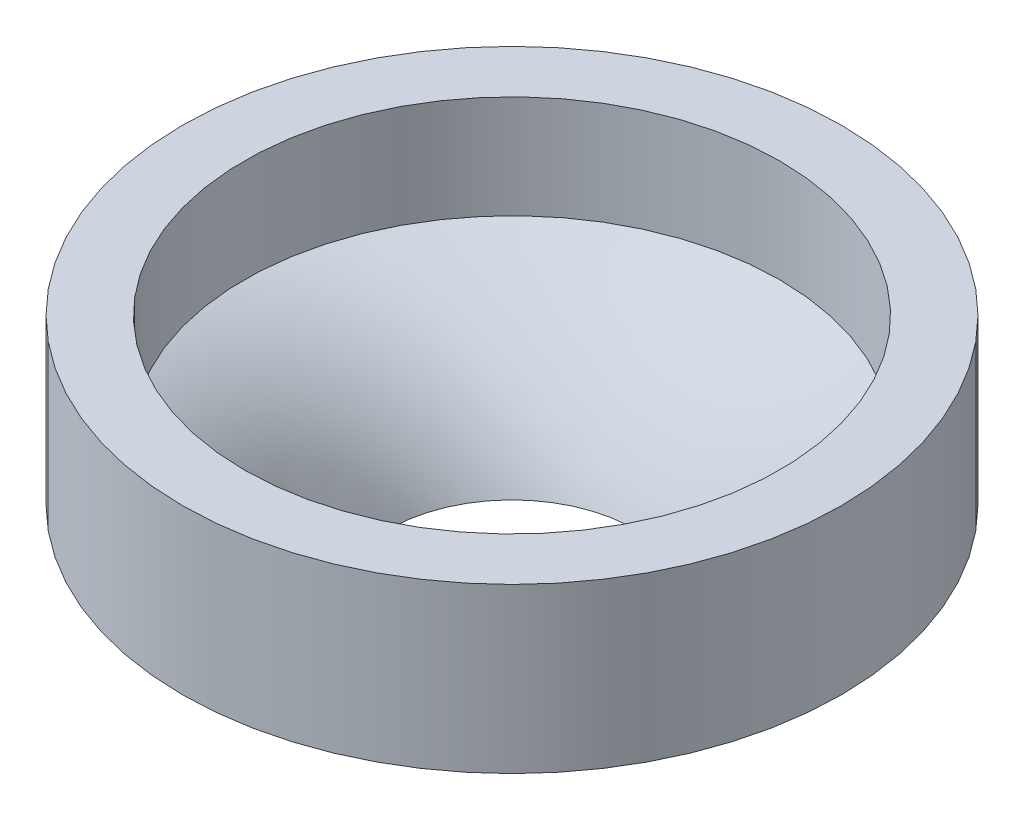
SolidWorks part; units mm, degrees
ref_plane "Front Plane" through (0, 0, 0) normal (0, 0, 1) x (1, 0, 0)
ref_plane "Top Plane" through (0, 0, 0) normal (0, 1, 0) x (1, 0, 0)
ref_plane "Right Plane" through (0, 0, 0) normal (1, 0, 0) x (0, 0, -1)
sketch "Sketch2" plane through (0, 0, 0) normal (1, 0, 0) x (0, 0, -1)
  line L0 (0, 40.9053) -> (0, -41.6717) construction
  line L1 (-79.0564, -40.2605) -> (-79.0564, -32.3059)
  line L2 (-76.0564, -37.3059) -> (-76.0564, -44.3059) construction
  line L3 (-69.0564, -44.3059) -> (-76.0564, -44.3059) construction
  line L4 (-76.0564, -37.3059) -> (-76.0564, -32.3059)
  line L5 (-79.0564, -32.3059) -> (-76.0564, -32.3059)
  line L6 (-69.0564, -44.3059) -> (-72.1486, -44.3059)
  line L7 (-63.0564, -32.3059) -> (-63.0564, -42.3059) construction
  arc A1 (-79.0564, -40.2605) -> (-72.1486, -44.3059) centre (-77.8197, -46.0692) cw
  arc A2 (-79.0564, -40.2605) -> (-71.9975, -44.8977) centre (-77.8197, -46.0692) cw construction
  arc A3 (-76.0564, -37.3059) -> (-69.0564, -44.3059) centre (-77.8197, -46.0692) cw construction
  arc A5 (-76.0564, -37.3059) -> (-69.0564, -44.3059) centre (-81.2566, -49.5061) cw
  dimension "D2" = 7
  dimension "D3" = 7
  dimension "D4" = 3
  dimension "D1" = 5
  dimension "13" = 13
revolve "Revolve1" add sketch "Sketch2" angle 360 about L7
